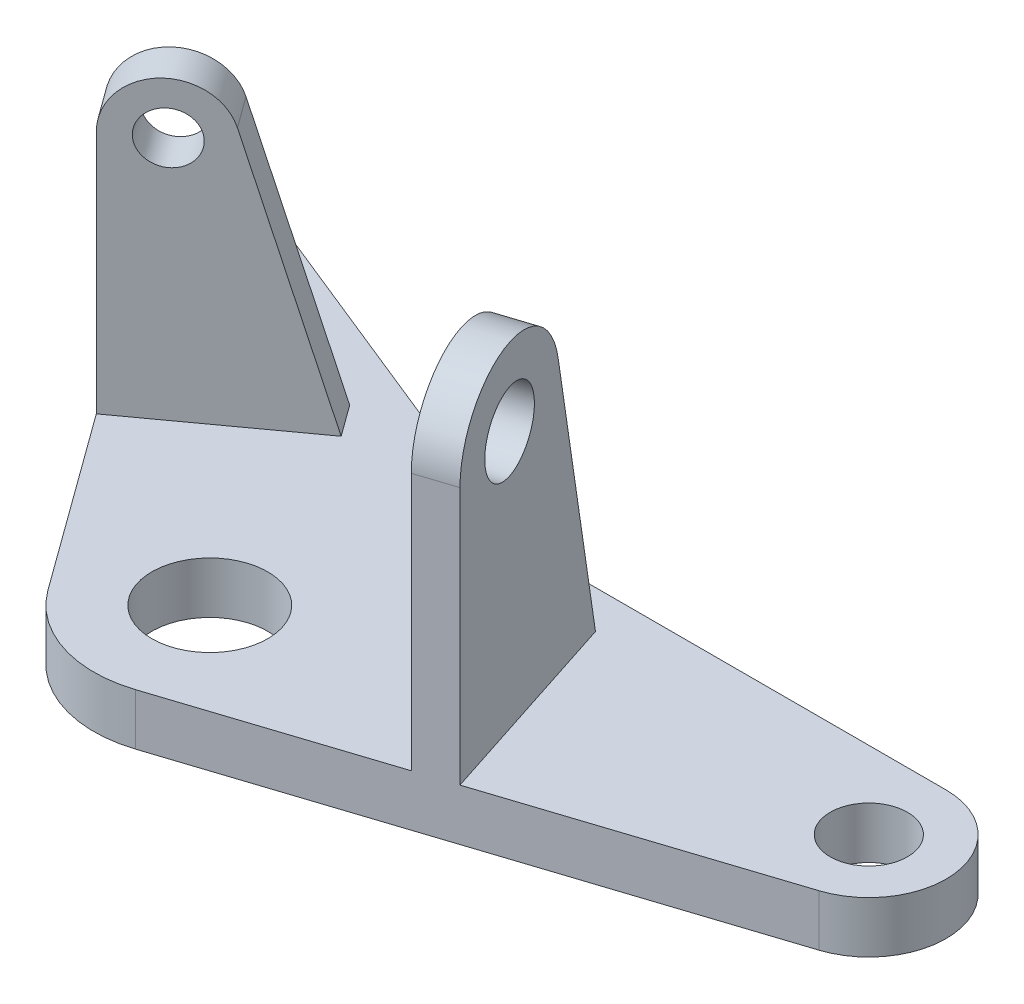
SolidWorks part; units mm, degrees
material "1060 Alloy"
ref_plane "Front Plane" through (0, 0, 0) normal (0, 0, 1) x (1, 0, 0)
ref_plane "Top Plane" through (0, 0, 0) normal (0, 1, 0) x (1, 0, 0)
ref_plane "Right Plane" through (0, 0, 0) normal (1, 0, 0) x (0, 0, -1)
sketch "Sketch1" plane through (0, 0, 0) normal (0, 1, 0) x (1, 0, 0)
  line L0 (-14.5623, -10.5801) -> (-54.4721, 44.351)
  line L1 (-45.0031, 56.4708) -> (7.1664, 35.3929)
  line L2 (22.8999, 32.3346) -> (82, 32.3346)
  line L3 (85.7082, 8.922) -> (5.5623, -17.119)
  line L4 (-48, 49.0533) -> (0, 0) construction
  line L5 (0, 0) -> (82, 20.3346) construction
  line L6 (-34.547, 16.9264) -> (-24.0358, 24.5633) construction
  line L7 (33.084, 8.2043) -> (37.8982, -6.6124) construction
  circle A0 centre (0, 0) radius 9
  circle A1 centre (-48, 49.0533) radius 4
  circle A2 centre (82, 20.3346) radius 6
  arc A3 (-54.4721, 44.351) -> (-45.0031, 56.4708) centre (-48, 49.0533) cw
  arc A4 (7.1664, 35.3929) -> (22.8999, 32.3346) centre (22.8999, 74.3346) ccw
  arc A5 (82, 32.3346) -> (85.7082, 8.922) centre (82, 20.3346) cw
  arc A6 (5.5623, -17.119) -> (-14.5623, -10.5801) centre (0, 0) cw
  dimension "D3" = 8
  dimension "D4" = 12
  dimension "D5" = 18
  dimension "D6" = 18
  dimension "D7" = 8
  dimension "D8" = 12
  dimension "D12" = 42
  dimension "D2" = 18
  dimension "D9" = 48
  dimension "D10" = 82
  dimension "D11" = 54
  dimension "D13" = 22
  dimension "D14" = 34
  dimension "D15" = 34
extrude "Boss-Extrude1" add sketch "Sketch1" along normal blind 8
ref_plane "Plane1" through (-19.9847, 0, -27.5066) normal (0.5878, 0, 0.809) x (0.809, 0, -0.5878)
ref_plane "Plane2" through (32.3359, 0, -10.5066) normal (-0.9511, 0, 0.309) x (0.309, 0, 0.9511)
sketch "Sketch2" plane through (-19.9847, 0, -27.5066) normal (0.5878, 0, 0.809) x (0.809, 0, -0.5878)
  line L0 (-18, 0) -> (-18, 46)
  line L1 (-2.3099, 48.2051) -> (11.5127, 0)
  line L2 (11.5127, 0) -> (-18, 0)
  arc A0 (-18, 46) -> (-2.3099, 48.2051) centre (-10, 46) cw
  circle A1 centre (-10, 46) radius 4
  dimension "D1" = 8
  dimension "D2" = 8
  dimension "D3" = 74
  dimension "D4" = 38
extrude "Boss-Extrude2" add sketch "Sketch2" against normal blind 6
sketch "Sketch3" plane through (32.3359, 0, -10.5066) normal (-0.9511, 0, 0.309) x (0.309, 0, 0.9511)
  line L0 (18, 0) -> (18, 48)
  line L1 (-5.7378, 50.4949) -> (-16.4708, 0)
  line L2 (-16.4708, 0) -> (18, 0)
  arc A0 (18, 48) -> (-5.7378, 50.4949) centre (6, 48) ccw
  circle A1 centre (6, 48) radius 6
  dimension "D1" = 12
  dimension "D2" = 12
  dimension "D3" = 48
  dimension "D4" = 78
extrude "Boss-Extrude3" add sketch "Sketch3" against normal blind 6
